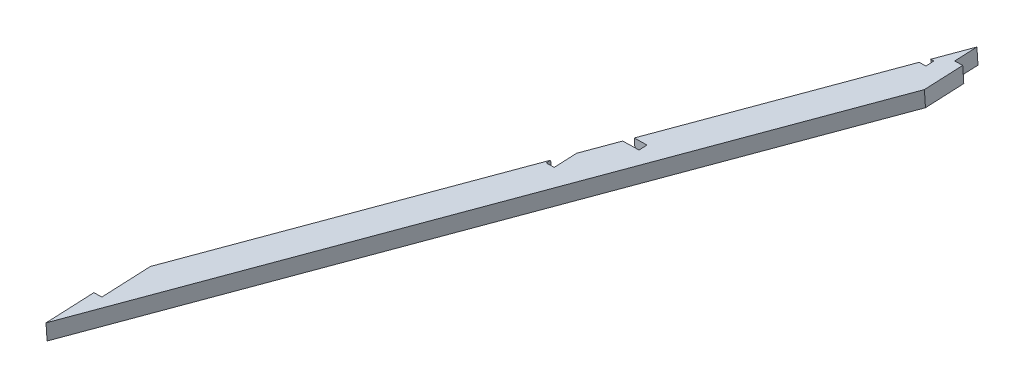
SolidWorks part; units mm, degrees
material "Balsa"
ref_plane "Front Plane" through (0, 0, 0) normal (0, 0, 1) x (1, 0, 0)
ref_plane "Top Plane" through (0, 0, 0) normal (0, 1, 0) x (1, 0, 0)
ref_plane "Right Plane" through (0, 0, 0) normal (1, 0, 0) x (0, 0, -1)
ref_plane "Plane2" through (-0.9047, 43.561, 2.0271) normal (-0.0207, 0.9987, 0.0465) x (0.9998, 0.0207, 0.0009)
sketch "Sketch1" plane through (-0.9047, 43.561, 2.0271) normal (-0.0207, 0.9987, 0.0465) x (0.9998, 0.0207, 0.0009)
  line L2 (267.6657, 90.8262) -> (267.6771, 394.5344)
  line L3 (267.6657, 90.8262) -> (267.6771, 394.5344) construction
  line L4 (375.3942, 337.5219) -> (267.6659, 95.8608)
  line L6 (375.3942, 337.5219) -> (375.3948, 352.7619)
  line L7 (372.2198, 361.5926) -> (366.5529, 348.8805)
  line L8 (267.6666, 114.9108) -> (267.6659, 95.8608)
  line L9 (372.2198, 361.5926) -> (372.2198, 352.7619)
  line L10 (372.2198, 352.7619) -> (375.3948, 352.7619)
  line L11 (375.3942, 337.5219) -> (375.3906, 242.5564) construction
  line L12 (270.8424, 134.1781) -> (270.8416, 114.9107)
  line L13 (270.8416, 114.9107) -> (267.6666, 114.9108)
  line L14 (267.6659, 95.8608) -> (267.6016, 95.7164) construction
  line L15 (323.1185, 251.4464) -> (323.1185, 242.5564)
  line L16 (323.1185, 242.5564) -> (319.9435, 242.5564)
  line L17 (319.9435, 242.5564) -> (319.9435, 244.3241)
  line L18 (319.9435, 244.3241) -> (270.8424, 134.1781)
  line L19 (267.6714, 242.5564) -> (375.3906, 242.5564) construction
  line L20 (328.7799, 264.1464) -> (335.2753, 264.1464)
  line L21 (335.2753, 264.1464) -> (335.2753, 267.3214)
  line L22 (335.2753, 267.3214) -> (330.1953, 267.3214)
  line L23 (365.1375, 345.7055) -> (367.8229, 345.7055)
  line L24 (367.8229, 345.7055) -> (367.8229, 348.8805)
  line L25 (367.8229, 348.8805) -> (366.5529, 348.8805)
  line L26 (328.7799, 264.1464) -> (323.1185, 251.4464)
  line L27 (365.1375, 345.7055) -> (330.1953, 267.3214)
  point P23 (321.531, 242.5564)
  point P24 (321.531, 242.5564)
  dimension "D1" = 12.7
  dimension "D2" = 15.24
  dimension "D3" = 3.175
  dimension "D4" = 3.175
  dimension "D5" = 19.05
  dimension "D6" = 3.175
  dimension "D7" = 8.89
  dimension "D8" = 3.175
  dimension "D9" = 1.27
  dimension "D10" = 3.175
  dimension "D11" = 12.7
  dimension "D12" = 5.08
extrude "Boss-Extrude1" add sketch "Sketch1" against normal blind 6.35
